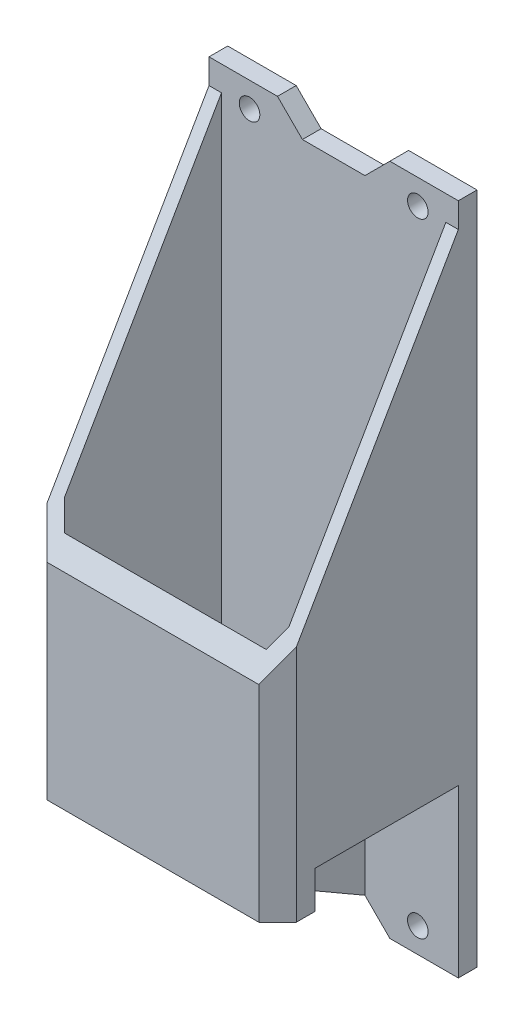
SolidWorks part; units mm, degrees
ref_plane "Front Plane" through (0, 0, 0) normal (0, 0, 1) x (1, 0, 0)
ref_plane "Top Plane" through (0, 0, 0) normal (0, 1, 0) x (1, 0, 0)
ref_plane "Right Plane" through (0, 0, 0) normal (1, 0, 0) x (0, 0, -1)
sketch "Sketch1" plane through (0, 0, 0) normal (0, 0, 1) x (1, 0, 0)
  line L0 (0, 0) -> (0, 100) construction
  line L1 (-20, 104) -> (-20, -4)
  line L2 (-20, 104) -> (-9.0147, 104)
  line L3 (-9.0147, 104) -> (-5.0147, 100)
  line L4 (-5.0147, 100) -> (5.0147, 100)
  line L5 (-20, -4) -> (-9.0147, -4)
  line L6 (-9.0147, -4) -> (-5.0147, 0)
  line L7 (-5.0147, 0) -> (5.0147, 0)
  line L8 (9.0147, -4) -> (5.0147, 0)
  line L9 (20, -4) -> (9.0147, -4)
  line L10 (9.0147, 104) -> (5.0147, 100)
  line L11 (20, 104) -> (9.0147, 104)
  line L12 (20, 104) -> (20, -4)
  circle A0 centre (-13.5, 100) radius 1.65
  circle A1 centre (-13.5, 0) radius 1.65
  circle A2 centre (13.5, 0) radius 1.65
  circle A3 centre (13.5, 100) radius 1.65
  point P7 (-8.9071, 103.6417)
  point P13 (-4.3871, 100)
  dimension "D2" = 3.3
  dimension "D1" = 100
  dimension "D3" = 13.5
  dimension "D4" = 20
  dimension "D5" = 45
  dimension "D6" = 45
  dimension "D7" = 4
  dimension "D8" = 4
  dimension "D9" = 6
  dimension "D10" = 6
extrude "Boss-Extrude1" add sketch "Sketch1" along normal blind 3
sketch "Sketch2" plane through (-20, 0, 0) normal (-1, 0, 0) x (0, 0, 1)
  line L0 (3, 0) -> (32, 16.7432)
  line L1 (3, 104) -> (3, -4) construction
  line L2 (32, 16.7432) -> (32, 49.7705)
  line L3 (32, 49.7705) -> (3, 100)
  line L4 (3, 100) -> (3, 0)
  line L5 (0, 104) -> (0, -4) construction
  point P8 (3, 99.3185)
  point P9 (28, 30.5454)
  point P10 (0, 0)
  point P12 (0, 0)
  dimension "D1" = 60
  dimension "D2" = 32
  dimension "D3" = 30
extrude "Boss-Extrude2" add sketch "Sketch2" against normal through all
chamfer "Chamfer1" distance 3 angle 45 2 edges at (-20, 33.2568, 32) (20, 33.2568, 32)
sketch "Sketch4" plane through (0, 0, 32) normal (0, 0, 1) x (1, 0, 0)
  line L0 (-5.0147, 0) -> (-5.0147, 16.7432)
  line L1 (-5.0147, 16.7432) -> (-20, 16.7432)
  line L2 (-20, 16.7432) -> (-20, 0)
  line L3 (-20, 0) -> (-5.0147, 0)
  line L4 (-5.0147, 0) -> (5.0147, 0) construction
  line L5 (20, 16.7432) -> (5.0147, 16.7432)
  line L6 (20, 16.7432) -> (20, 0)
  line L7 (20, 0) -> (5.0147, 0)
  line L8 (5.0147, 16.7432) -> (5.0147, 0)
  line L9 (-3.0147, 0) -> (3.0147, 0)
  line L10 (-3.0147, 0) -> (-3.0147, 16.7432)
  line L11 (-3.0147, 16.7432) -> (3.0147, 16.7432)
  line L12 (3.0147, 0) -> (3.0147, 16.7432)
  line L13 (17, 16.7432) -> (-17, 16.7432) construction
  point P19 (0, 0)
  point P20 (0, 0)
  dimension "D1" = 2
  dimension "D2" = 2
extrude "Cut-Extrude3" cut sketch "Sketch4" against normal up to surface (29 mm away)
sketch "Sketch5" plane through (0, 104, 0) normal (0, 1, 0) x (1, 0, 0)
  line L0 (18, -3) -> (18, -28.1716)
  line L1 (20, -3) -> (15.15, -3) construction
  line L2 (18, -28.1716) -> (16.1716, -30)
  line L3 (16.1716, -30) -> (-16.1716, -30)
  line L4 (-16.1716, -30) -> (-18, -28.1716)
  line L5 (-18, -28.1716) -> (-18, -3)
  line L6 (-15.15, -3) -> (-20, -3) construction
  line L7 (-18, -3) -> (18, -3)
  line L8 (20, -29) -> (20, -3) construction
  line L9 (-20, -29) -> (-20, -3) construction
  line L10 (17, -32) -> (20, -29) construction
  line L11 (-20, -29) -> (-17, -32) construction
  line L12 (17, -32) -> (-17, -32) construction
  dimension "D1" = 2
  dimension "D2" = 2
  dimension "D3" = 2
  dimension "D4" = 2
  dimension "D5" = 2
extrude "Cut-Extrude4" cut sketch "Sketch5" against normal blind 86
sketch "Sketch6" plane through (0, 16.7432, 0) normal (0, -1, 0) x (-1, 0, 0)
  line L0 (5.0147, -29) -> (15.7574, -29)
  line L1 (5.0147, -3) -> (5.0147, -32) construction
  line L2 (15.7574, -29) -> (18.7574, -26)
  line L3 (18.7574, -26) -> (20.7574, -26)
  line L4 (20.7574, -26) -> (20.7574, -3)
  line L5 (20.7574, -3) -> (5.0147, -3)
  line L6 (5.0147, -3) -> (5.0147, -29)
  line L7 (17, -32) -> (20, -29) construction
  line L8 (5.0147, -32) -> (17, -32) construction
  line L9 (0, 0) -> (0, -32) construction
  line L10 (-3.0147, -32) -> (3.0147, -32) construction
  line L11 (-5.0147, -3) -> (-5.0147, -29)
  line L12 (-20.7574, -3) -> (-5.0147, -3)
  line L13 (-20.7574, -26) -> (-20.7574, -3)
  line L14 (-18.7574, -26) -> (-20.7574, -26)
  line L15 (-15.7574, -29) -> (-18.7574, -26)
  line L16 (-5.0147, -29) -> (-15.7574, -29)
  dimension "D1" = 3
  dimension "D2" = 3
  dimension "D3" = 3
  dimension "D4" = 2
extrude "Cut-Extrude5" cut sketch "Sketch6" against normal blind 6
sketch "Sketch7" plane through (0, 100, 0) normal (0, 1, 0) x (1, 0, 0)
  line L1 (-17.3287, -3.1642) -> (16.6713, -3.1642)
  line L2 (-17.3287, -3.1642) -> (-17.3287, -28.1642)
  line L3 (-17.3287, -28.1642) -> (16.6713, -28.1642)
  line L4 (16.6713, -3.1642) -> (16.6713, -28.1642)
  line L5 (-17.3287, -3.1642) -> (16.6713, -28.1642) construction
  line L6 (-17.3287, -28.1642) -> (16.6713, -3.1642) construction
  point P0 (-0.3287, -15.6642)
  point P5 (-0.3287, -15.6642)
  dimension "D1" = 34
  dimension "D2" = 25
